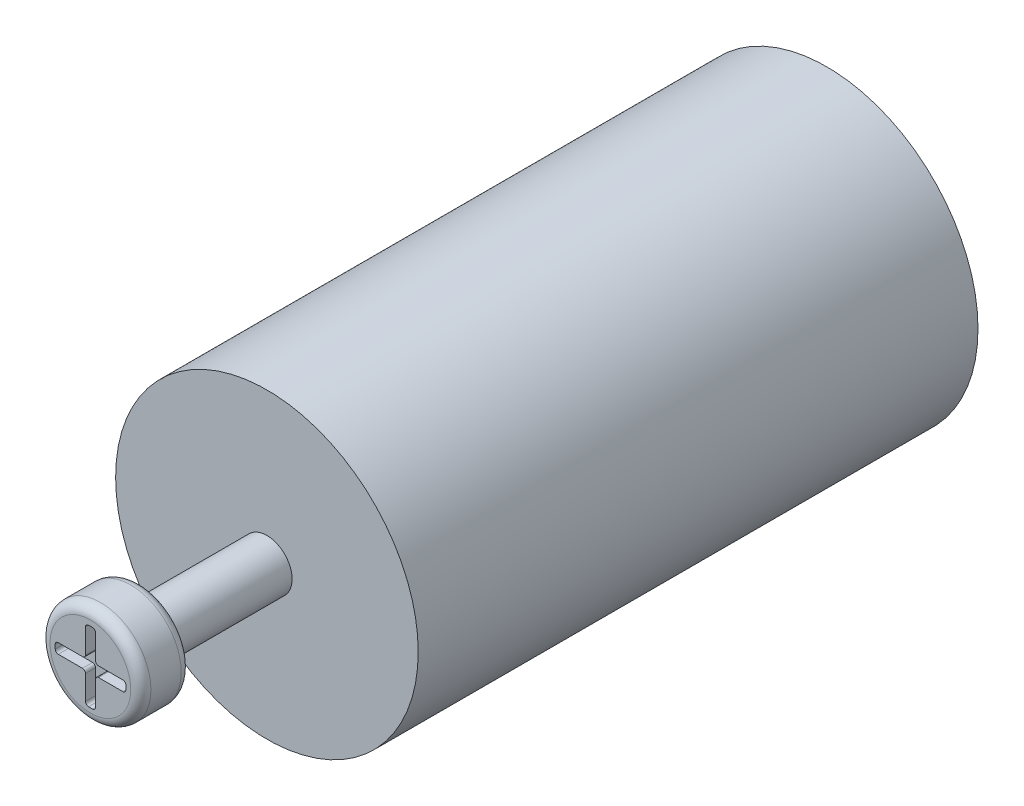
SolidWorks part; units mm, degrees
ref_plane "Front Plane" through (0, 0, 0) normal (0, 0, 1) x (1, 0, 0)
ref_plane "Top Plane" through (0, 0, 0) normal (0, 1, 0) x (1, 0, 0)
ref_plane "Right Plane" through (0, 0, 0) normal (1, 0, 0) x (0, 0, -1)
sketch "Sketch1" plane through (0, 0, 0) normal (0, 0, 1) x (1, 0, 0)
  circle A0 centre (0, 0) radius 6.35
extrude "Boss-Extrude1" add sketch "Sketch1" along normal blind 6.35
sketch "Sketch2" plane through (0, 0, 6.35) normal (0, 0, 1) x (1, 0, 0)
  circle A0 centre (0, 0) radius 38.1
extrude "Boss-Extrude2" add sketch "Sketch2" along normal blind 140.97
sketch "Sketch3" plane through (0, 0, 147.32) normal (0, 0, 1) x (1, 0, 0)
  circle A0 centre (0, 0) radius 6.35
extrude "Boss-Extrude3" add sketch "Sketch3" along normal blind 31.75
sketch "Sketch4" plane through (0, 0, 179.07) normal (0, 0, 1) x (1, 0, 0)
  circle A0 centre (0, 0) radius 12.7
extrude "Boss-Extrude4" add sketch "Sketch4" along normal blind 12.7
fillet "Fillet1" radius 2.54 3 edges at (6.35, 0, 179.07) (12.7, 0, 179.07) (12.7, 0, 191.77)
sketch "Sketch5" plane through (0, 0, 191.77) normal (0, 0, 1) x (1, 0, 0)
  line L0 (-0.4753, 8.7766) -> (0.5407, 8.7766)
  line L1 (-1.2373, 8.0146) -> (-1.2373, 1.9186)
  line L2 (-0.4753, -9.0034) -> (0.5407, -9.0034)
  line L3 (1.3027, 8.0146) -> (1.3027, 1.9186)
  line L4 (-8.0953, 1.1566) -> (-1.9993, 1.1566)
  line L5 (-8.8573, 0.3946) -> (-8.8573, -0.6214)
  line L6 (-8.0953, -1.3834) -> (-1.9993, -1.3834)
  line L7 (8.9227, 0.3946) -> (8.9227, -0.6214)
  line L8 (1.3027, -2.1454) -> (1.3027, -8.2414)
  line L9 (-1.2373, -2.1454) -> (-1.2373, -8.2414)
  line L10 (2.0647, -1.3834) -> (8.1607, -1.3834)
  line L11 (2.0647, 1.1566) -> (8.1607, 1.1566)
  arc A0 (-8.8573, -0.6214) -> (-8.0953, -1.3834) centre (-8.0953, -0.6214) ccw
  arc A1 (-1.2373, -2.1454) -> (-1.9993, -1.3834) centre (-1.9993, -2.1454) ccw
  arc A2 (1.3027, -2.1454) -> (2.0647, -1.3834) centre (2.0647, -2.1454) cw
  arc A3 (-0.4753, -9.0034) -> (-1.2373, -8.2414) centre (-0.4753, -8.2414) cw
  arc A4 (0.5407, -9.0034) -> (1.3027, -8.2414) centre (0.5407, -8.2414) ccw
  arc A5 (8.9227, 0.3946) -> (8.1607, 1.1566) centre (8.1607, 0.3946) ccw
  arc A6 (8.9227, -0.6214) -> (8.1607, -1.3834) centre (8.1607, -0.6214) cw
  arc A7 (-1.2373, 8.0146) -> (-0.4753, 8.7766) centre (-0.4753, 8.0146) cw
  arc A8 (-8.8573, 0.3946) -> (-8.0953, 1.1566) centre (-8.0953, 0.3946) cw
  arc A9 (1.3027, 8.0146) -> (0.5407, 8.7766) centre (0.5407, 8.0146) ccw
  arc A10 (2.0647, 1.1566) -> (1.3027, 1.9186) centre (2.0647, 1.9186) cw
  arc A11 (-1.2373, 1.9186) -> (-1.9993, 1.1566) centre (-1.9993, 1.9186) cw
  point P0 (-0.6553, 0.3946)
  point P5 (-1.2373, 0.846)
  point P38 (0, -1.352)
  point P39 (-0.5821, -0.9006)
  dimension "D1" = 0.762
  dimension "D2" = 0.762
  dimension "D3" = 0.762
extrude "Cut-Extrude1" cut sketch "Sketch5" against normal blind 2.54
